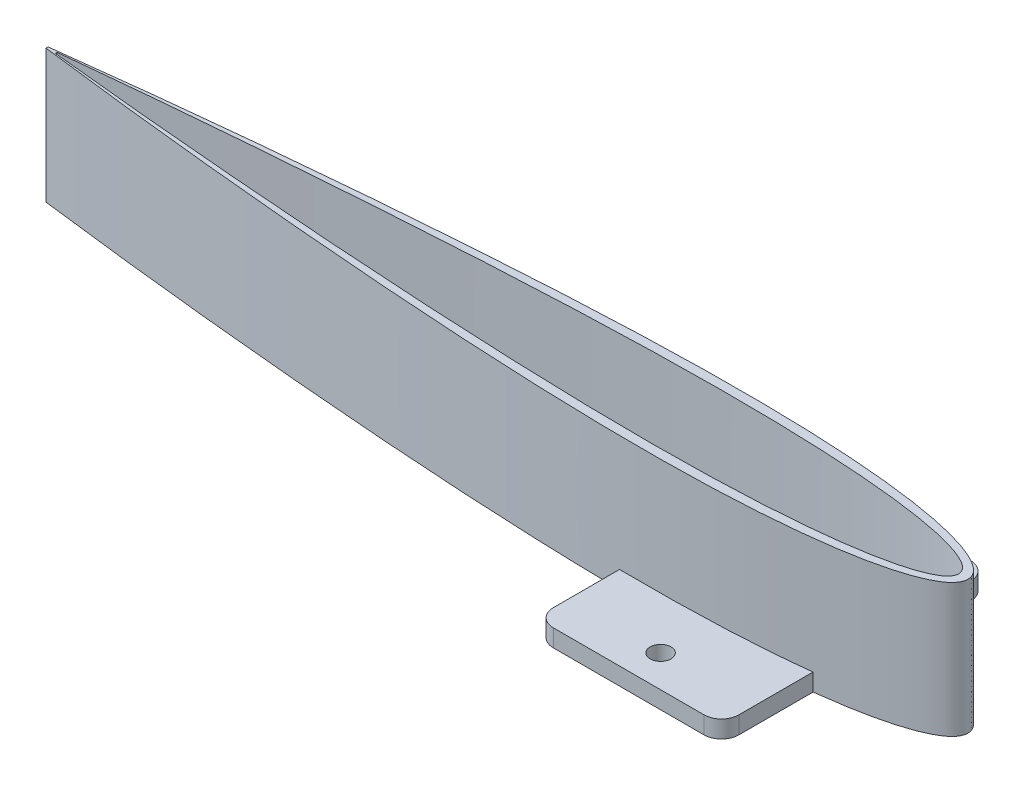
SolidWorks part; units mm, degrees
ref_plane "Front Plane" through (0, 0, 0) normal (0, 0, 1) x (1, 0, 0)
ref_plane "Top Plane" through (0, 0, 0) normal (0, 1, 0) x (1, 0, 0)
ref_plane "Right Plane" through (0, 0, 0) normal (1, 0, 0) x (0, 0, -1)
sketch "Sketch1" plane through (0, 0, 0) normal (0, 1, 0) x (1, 0, 0)
  line L0 (-157.192, 0.1806) -> (-157.192, -0.1806)
  spline S0 degree 3 poles (-157.192, 0.1806) (-157.047, 0.199) (-156.4687, 0.2722) (-155.1736, 0.4348) (-153.0307, 0.7004) (-150.0636, 1.061) (-146.3047, 1.5064) (-141.7952, 2.0244) (-136.5846, 2.602) (-130.7298, 3.2251) (-124.295, 3.8796) (-117.3509, 4.5506) (-109.9733, 5.2233) (-102.2433, 5.8819) (-94.2454, 6.5099) (-86.0672, 7.0899) (-77.7984, 7.6036) (-69.5295, 8.0323) (-61.3508, 8.3573) (-53.352, 8.5612) (-45.6206, 8.6288) (-38.2411, 8.5483) (-31.2943, 8.3123) (-24.856, 7.9186) (-18.9963, 7.3705) (-13.7789, 6.6763) (-9.2587, 5.8499) (-5.4833, 4.9066) (-2.4807, 3.868) (-0.2761, 2.7381) (1.1891, 1.5155) (1.7783, 0) (1.1891, -1.5155) (-0.2761, -2.7381) (-2.4807, -3.868) (-5.4833, -4.9066) (-9.2587, -5.8499) (-13.7789, -6.6763) (-18.9963, -7.3705) (-24.856, -7.9186) (-31.2943, -8.3123) (-38.2411, -8.5483) (-45.6206, -8.6288) (-53.352, -8.5612) (-61.3508, -8.3573) (-69.5295, -8.0323) (-77.7984, -7.6036) (-86.0672, -7.0899) (-94.2454, -6.5099) (-102.2433, -5.8819) (-109.9733, -5.2233) (-117.3509, -4.5506) (-124.295, -3.8796) (-130.7298, -3.2251) (-136.5846, -2.602) (-141.7952, -2.0244) (-146.3047, -1.5064) (-150.0636, -1.061) (-153.0307, -0.7004) (-155.1736, -0.4348) (-156.4687, -0.2722) (-157.047, -0.199) (-157.192, -0.1806) knots 0 0 0 0 0.001358 0.005418 0.012133 0.021428 0.033198 0.047314 0.063616 0.081925 0.102038 0.123732 0.146768 0.170892 0.195839 0.221333 0.247094 0.27284 0.29829 0.323168 0.347206 0.370149 0.391755 0.411804 0.430092 0.446444 0.46071 0.472778 0.482587 0.490166 0.495733 0.5 0.504267 0.509834 0.517413 0.527222 0.53929 0.553556 0.569908 0.588196 0.608245 0.629851 0.652794 0.676832 0.70171 0.72716 0.752906 0.778667 0.804161 0.829108 0.853232 0.876268 0.897962 0.918075 0.936384 0.952686 0.966802 0.978572 0.987867 0.994582 0.998642 1 1 1 1
extrude "Boss-Extrude1" add sketch "Sketch1" along normal blind 23
sketch "Sketch2" plane through (0, 0, 0) normal (0, 1, 0) x (1, 0, 0)
  line L0 (-46.9, -23) -> (-20.9, -23)
  line L1 (-17.9, -20) -> (-17.9, 20)
  line L2 (-20.9, 23) -> (-46.9, 23)
  line L3 (-49.9, 20) -> (-49.9, -20)
  arc A0 (-20.9, -23) -> (-17.9, -20) centre (-20.9, -20) ccw
  arc A1 (-17.9, 20) -> (-20.9, 23) centre (-20.9, 20) ccw
  arc A2 (-46.9, 23) -> (-49.9, 20) centre (-46.9, 20) ccw
  arc A3 (-49.9, -20) -> (-46.9, -23) centre (-46.9, -20) ccw
extrude "Boss-Extrude2" add sketch "Sketch2" along normal blind 3
ref_plane "Plane1" through (0, 23, 0) normal (0, 1, 0) x (1, 0, 0)
sketch "Sketch3" plane through (0, 23, 0) normal (0, 1, 0) x (1, 0, 0)
  line L0 (-155.592, 0.147) -> (-155.592, -0.147)
  spline S0 degree 3 poles (-155.592, 0.147) (-155.4499, 0.162) (-154.8833, 0.2215) (-153.6142, 0.3539) (-151.5144, 0.5701) (-148.607, 0.8637) (-144.9238, 1.2262) (-140.5052, 1.6479) (-135.3994, 2.118) (-129.6626, 2.6253) (-123.3575, 3.158) (-116.5532, 3.7042) (-109.3243, 4.2517) (-101.7499, 4.7878) (-93.9132, 5.299) (-85.8998, 5.7712) (-77.7976, 6.1893) (-69.6954, 6.5382) (-61.6817, 6.8027) (-53.8443, 6.9687) (-46.269, 7.0237) (-39.0388, 6.9582) (-32.2327, 6.7662) (-25.9252, 6.4458) (-20.185, 5.9999) (-15.0747, 5.4351) (-10.6484, 4.7636) (-6.9542, 3.9959) (-4.0194, 3.1583) (-1.8752, 2.2388) (-0.4468, 1.2888) (0.1847, 0) (-0.4468, -1.2888) (-1.8752, -2.2388) (-4.0194, -3.1583) (-6.9542, -3.9959) (-10.6484, -4.7636) (-15.0747, -5.4351) (-20.185, -5.9999) (-25.9252, -6.4458) (-32.2327, -6.7662) (-39.0388, -6.9582) (-46.269, -7.0237) (-53.8443, -6.9687) (-61.6817, -6.8027) (-69.6954, -6.5382) (-77.7976, -6.1893) (-85.8998, -5.7712) (-93.9132, -5.299) (-101.7499, -4.7878) (-109.3243, -4.2517) (-116.5532, -3.7042) (-123.3575, -3.158) (-129.6626, -2.6253) (-135.3994, -2.118) (-140.5052, -1.6479) (-144.9238, -1.2262) (-148.607, -0.8637) (-151.5144, -0.5701) (-153.6142, -0.3539) (-154.8833, -0.2215) (-155.4499, -0.162) (-155.592, -0.147) knots 0 0 0 0 0.001361 0.005428 0.012156 0.02147 0.033267 0.047415 0.063758 0.082114 0.102282 0.124039 0.147146 0.171348 0.196379 0.221963 0.247821 0.273669 0.299223 0.324206 0.348349 0.37139 0.393087 0.41321 0.431552 0.447929 0.462182 0.474186 0.48386 0.491199 0.496361 0.5 0.503639 0.508801 0.51614 0.525814 0.537818 0.552071 0.568448 0.58679 0.606913 0.62861 0.651651 0.675794 0.700777 0.726331 0.752179 0.778037 0.803621 0.828652 0.852854 0.875961 0.897718 0.917886 0.936242 0.952585 0.966733 0.97853 0.987844 0.994572 0.998639 1 1 1 1
extrude "Cut-Extrude1" cut sketch "Sketch3" against normal blind 20
sketch "Sketch4" plane through (0, 0, 0) normal (0, 1, 0) x (1, 0, 0)
  circle A0 centre (-33.9, -17.5) radius 1.8
  circle A1 centre (-33.9, 17.5) radius 1.8
extrude "Cut-Extrude2" cut sketch "Sketch4" along normal blind 3
